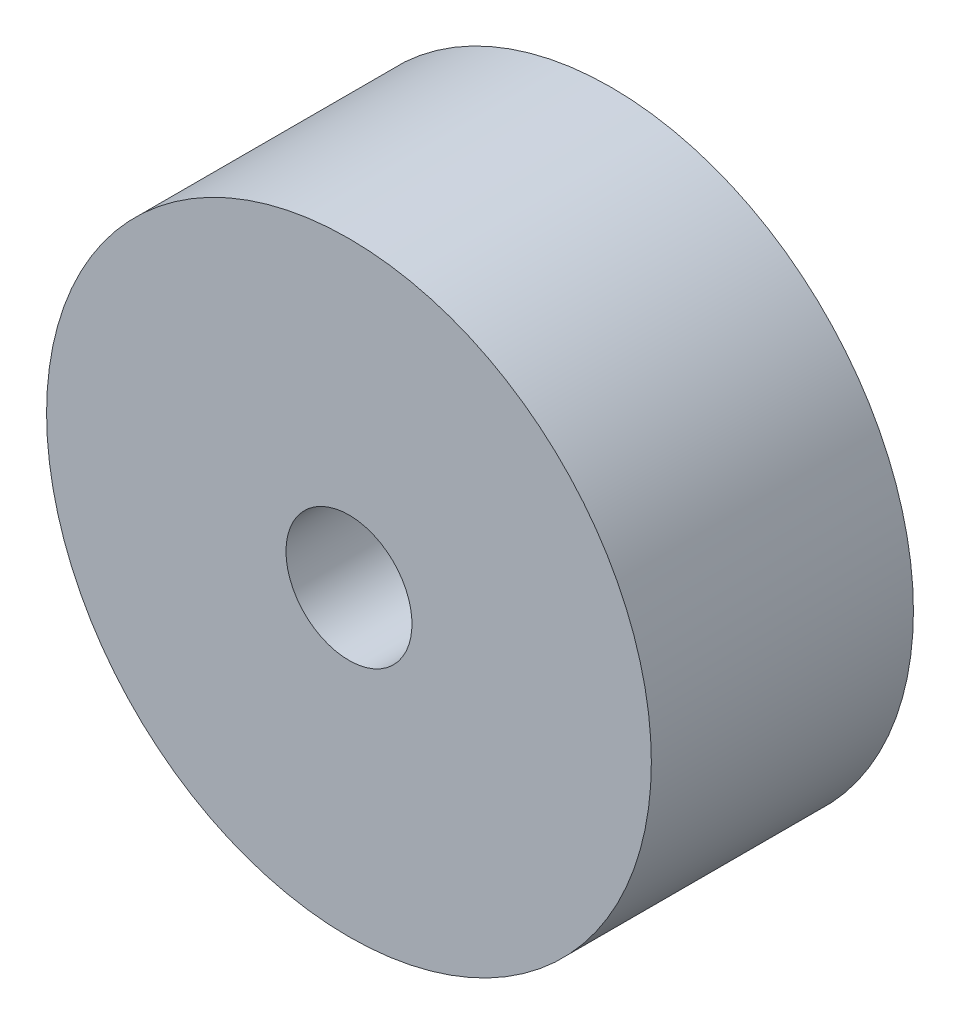
SolidWorks part; units mm, degrees
ref_plane "Front Plane" through (0, 0, 0) normal (0, 0, 1) x (1, 0, 0)
ref_plane "Top Plane" through (0, 0, 0) normal (0, 1, 0) x (1, 0, 0)
ref_plane "Right Plane" through (0, 0, 0) normal (1, 0, 0) x (0, 0, -1)
sketch "Sketch1" plane through (0, 0, 0) normal (0, 0, 1) x (1, 0, 0)
  circle A0 centre (0, 0) radius 30
  circle A1 centre (0, 0) radius 6.25
  dimension "D1" = 60
  dimension "D2" = 12.5
extrude "Boss-Extrude1" add sketch "Sketch1" along normal blind 26
